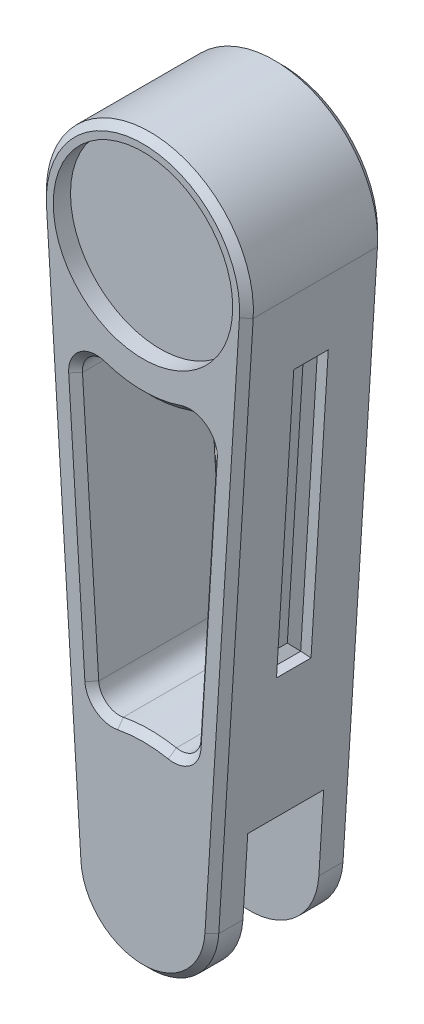
SolidWorks part; units mm, degrees
ref_plane "Front Plane" through (0, 0, 0) normal (0, 0, 1) x (1, 0, 0)
ref_plane "Top Plane" through (0, 0, 0) normal (0, 1, 0) x (1, 0, 0)
ref_plane "Right Plane" through (0, 0, 0) normal (1, 0, 0) x (0, 0, -1)
sketch "Sketch1" plane through (0, 0, 0) normal (0, 0, 1) x (1, 0, 0)
  line L0 (0, 0) -> (0, -160) construction
  line L1 (-29.9413, -1.875) -> (-19.9609, -161.25)
  line L2 (29.9413, -1.875) -> (19.9609, -161.25)
  arc A0 (29.9413, -1.875) -> (-29.9413, -1.875) centre (0, 0) ccw
  arc A1 (-19.9609, -161.25) -> (19.9609, -161.25) centre (0, -160) ccw
  dimension "D1" = 60
  dimension "D3" = 40
  dimension "D2" = 160
extrude "Boss-Extrude1" add sketch "Sketch1" along normal mid plane 40
sketch "Sketch2" plane through (0, 0, -20) normal (0, 0, -1) x (-1, 0, 0)
  circle A0 centre (0, 0) radius 26
  dimension "D1" = 52
extrude "Cut-Extrude1" cut sketch "Sketch2" against normal blind 5
sketch "Sketch3" plane through (0, 0, 0) normal (0, 0, 1) x (1, 0, 0)
  circle A0 centre (0, -160) radius 30
  dimension "D1" = 60
extrude "Cut-Extrude2" cut sketch "Sketch3" against normal mid plane 22
sketch "Sketch4" plane through (0, 0, -20) normal (0, 0, -1) x (-1, 0, 0)
  line L4 (-21.957, -1.375) -> (-11.9765, -160.75)
  line L5 (11.9765, -160.75) -> (21.957, -1.375)
  line L6 (-20.176, -29.8149) -> (-14.3614, -122.667)
  line L7 (14.3614, -122.667) -> (20.176, -29.8149)
  line L8 (-21.3584, -138.933) -> (-19.9609, -161.25)
  line L9 (19.9609, -161.25) -> (21.3584, -138.933)
  line L10 (-21.3584, -138.933) -> (-19.9609, -161.25)
  line L11 (19.9609, -161.25) -> (21.3584, -138.933)
  arc A0 (19.2297, -124.9256) -> (-19.2297, -124.9256) centre (0, -160) ccw construction
  arc A1 (14.3614, -122.667) -> (-14.3614, -122.667) centre (0, -160) ccw
  circle A2 centre (0, 0) radius 36
  arc A3 (-20.176, -29.8149) -> (20.176, -29.8149) centre (0, 0) ccw
  arc A4 (21.957, -1.375) -> (-21.957, -1.375) centre (0, 0) ccw
  arc A5 (-11.9765, -160.75) -> (11.9765, -160.75) centre (0, -160) ccw
  arc A8 (21.3584, -138.933) -> (-21.3584, -138.933) centre (0, -160) ccw
  arc A9 (-19.9609, -161.25) -> (19.9609, -161.25) centre (0, -160) ccw
  arc A10 (14.4223, -133.6942) -> (-14.4223, -133.6942) centre (0, -160) ccw construction
  arc A11 (-19.9609, -161.25) -> (19.9609, -161.25) centre (0, -160) ccw
  dimension "D1" = 8
  dimension "D2" = 0
  dimension "D3" = 10
  dimension "D4" = 10
extrude "Cut-Extrude3" cut sketch "Sketch4" against normal through all contours A3 L6 A1 L7
fillet "Fillet1" radius 6 4 edges at (14.3614, -122.667, 0) (-14.3614, -122.667, 0) (20.176, -29.8149, 0) (-20.176, -29.8149, 0)
chamfer "Chamfer1" distance 2 angle 45 24 edges at (12.5053, -119.6065, 20) (17.1785, -77.6821, 20) (17.1848, -34.9897, 20) (0, -36, 20) (-17.1848, -34.9897, 20) (-17.1785, -77.6821, 20) (-12.5053, -119.6065, 20) (0, -120, 20) (24.9511, -81.5625, 20) (0, -180, 20) (-24.9511, -81.5625, 20) (0, 30, 20) (24.9511, -81.5625, -20) (0, 30, -20) (0, -180, -20) (-24.9511, -81.5625, -20) (17.1785, -77.6821, -20) (12.5053, -119.6065, -20) (17.1848, -34.9897, -20) (0, -120, -20) (0, -36, -20) (-12.5053, -119.6065, -20) (-17.1848, -34.9897, -20) (-17.1785, -77.6821, -20)
sketch "Sketch6" plane through (29.9413, -1.875, 0) normal (0.998, -0.0625, 0) x (0, 0, -1)
  line L0 (0, 0) -> (0, -100) construction
  line L1 (-5, -20) -> (5, -20)
  line L2 (-5, -20) -> (-5, -100)
  line L3 (-5, -100) -> (5, -100)
  line L4 (5, -20) -> (5, -100)
  line L5 (-18, 0) -> (18, 0) construction
  dimension "D1" = 20
  dimension "D2" = 80
  dimension "D3" = 10
extrude "Cut-Extrude4" cut sketch "Sketch6" against normal blind 5
chamfer "Chamfer2" distance 2 angle 45 4 edges at (23.7011, -21.5234, 0) (21.2011, -61.4452, -5) (18.7011, -101.367, 0) (21.2011, -61.4452, 5)
sketch "Sketch7" plane through (0, 0, 20) normal (0, 0, 1) x (1, 0, 0)
  circle A0 centre (0, -160) radius 10
  arc A1 (-19.9609, -161.25) -> (19.9609, -161.25) centre (0, -160) ccw construction
  circle A2 centre (0, 0) radius 20
  arc A3 (29.9413, -1.875) -> (-29.9413, -1.875) centre (0, 0) ccw construction
  dimension "D1" = 10
  dimension "D2" = 10
extrude "Cut-Extrude5" cut sketch "Sketch7" against normal blind 5
chamfer "Chamfer3" distance 2 angle 45 4 edges at (10, -160, 20) (10, -160, 15) (20, 0, 15) (20, 0, 20)
mirror "Mirror1" about plane through (0, 0, 0) normal (0, 0, 1) of bodies 106
delete or keep bodies "Body-Delete/Keep 1" type delete bodies bodies 106
sketch "Sketch8" plane through (0, 0, 0) normal (0, 0, 1) x (1, 0, 0)
  line L0 (0, 30) -> (0, -180) construction
  arc A0 (29.9413, -1.875) -> (-29.9413, -1.875) centre (0, 0) ccw construction
  arc A1 (-19.9609, -161.25) -> (19.9609, -161.25) centre (0, -160) ccw construction
  point P8 (0, -75)
